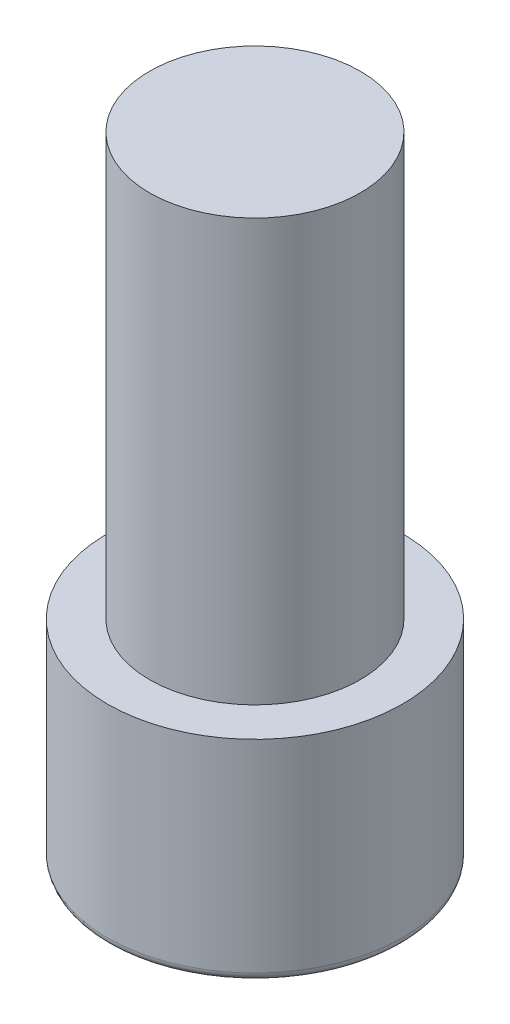
SolidWorks part; units mm, degrees
ref_plane "Front Plane" through (0, 0, 0) normal (0, 0, 1) x (1, 0, 0)
ref_plane "Top Plane" through (0, 0, 0) normal (0, 1, 0) x (1, 0, 0)
ref_plane "Right Plane" through (0, 0, 0) normal (1, 0, 0) x (0, 0, -1)
sketch "Sketch1" plane through (0, 0, 0) normal (0, 1, 0) x (1, 0, 0)
  circle A0 centre (0, 0) radius 3.5
  dimension "D1" = 7
extrude "Boss-Extrude1" add sketch "Sketch1" along normal blind 5
sketch "Sketch2" plane through (0, 5, 0) normal (0, 1, 0) x (1, 0, 0)
  circle A1 centre (0, 0) radius 2.5
extrude "Boss-Extrude2" add sketch "Sketch2" along normal blind 10
sketch "Sketch3" plane through (0, 0, 0) normal (0, -1, 0) x (1, 0, 0)
  line L1 (0, 2) -> (-1.7321, 1)
  line L2 (-1.7321, 1) -> (-1.7321, -1)
  line L3 (-1.7321, -1) -> (0, -2)
  line L4 (0, -2) -> (1.7321, -1)
  line L5 (1.7321, -1) -> (1.7321, 1)
  line L6 (1.7321, 1) -> (0, 2)
  circle A0 centre (0, 0) radius 1.7321 construction
  dimension "D1" = 2
extrude "Cut-Extrude1" cut sketch "Sketch3" against normal blind 2
chamfer "Chamfer1" distance 0.25 angle 45 6 edges at (1.7321, 0, 0) (0.866, 0, -1.5) (-0.866, 0, -1.5) (-1.7321, 0, 0) (-0.866, 0, 1.5) (0.866, 0, 1.5)
fillet "Fillet1" radius 0.2 1 edges at (0, 0, 3.5)
